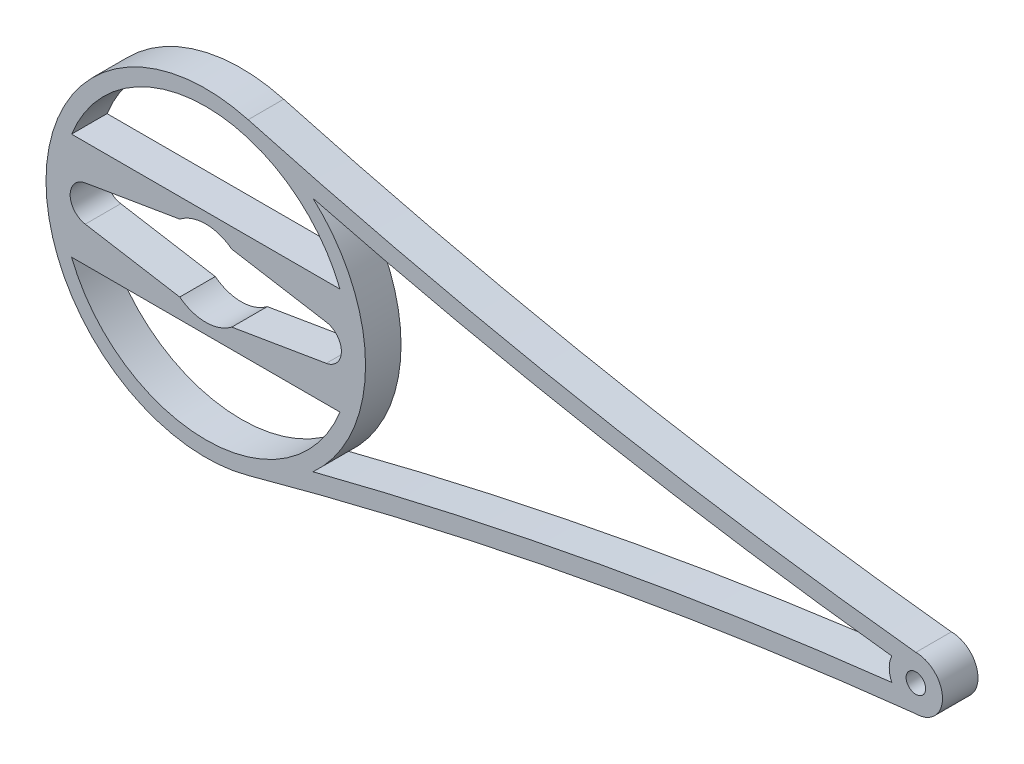
SolidWorks part; units mm, degrees
material "ABS"
ref_plane "Front Plane" through (0, 0, 0) normal (0, 0, 1) x (1, 0, 0)
ref_plane "Top Plane" through (0, 0, 0) normal (0, 1, 0) x (1, 0, 0)
ref_plane "Right Plane" through (0, 0, 0) normal (1, 0, 0) x (0, 0, -1)
sketch "Sketch3" plane through (0, 0, 0) normal (0, 0, 1) x (1, 0, 0)
  line L0 (0, 0) -> (100, 0) construction
  line L1 (18.9, 0) -> (18.9, 7.5) construction
  line L2 (-18.9, -7.5) -> (18.9, -7.5)
  line L3 (-18.9, -7.5) -> (-18.9, 7.5) construction
  line L4 (-18.9, 7.5) -> (18.9, 7.5)
  line L5 (18.9, -7.5) -> (18.9, 0) construction
  arc A0 (5.9672, 21.6943) -> (5.9672, -21.6943) centre (0, 0) ccw
  arc A1 (-18.9, -7.5) -> (18.9, -7.5) centre (0, 0) ccw
  arc A2 (100, -3.75) -> (100, 3.75) centre (100, 0) ccw
  arc A3 (5.9672, 21.6943) -> (100, 3.75) centre (165.0937, 600.2086) ccw
  arc A4 (15.1042, 16.6767) -> (96.6145, 1.6128) centre (165.0937, 600.2086) ccw
  arc A5 (5.3042, 19.2838) -> (99.7288, 1.2648) centre (165.0937, 600.2086) ccw construction
  arc A6 (15.1042, -16.6767) -> (96.6145, -1.6128) centre (165.0937, -600.2086) cw
  arc A7 (5.9672, -21.6943) -> (100, -3.75) centre (165.0937, -600.2086) cw
  arc A8 (96.6145, -1.6128) -> (100, -3.75) centre (100, 0) ccw construction
  arc A9 (100, 3.75) -> (96.6145, 1.6128) centre (100, 0) ccw construction
  arc A10 (96.6145, 1.6128) -> (96.6145, -1.6128) centre (100, 0) ccw
  arc A11 (15.1042, 16.6767) -> (5.9672, 21.6943) centre (0, 0) ccw construction
  arc A12 (5.9672, -21.6943) -> (15.1042, -16.6767) centre (0, 0) ccw construction
  arc A13 (15.1042, -16.6767) -> (15.1042, 16.6767) centre (0, 0) ccw
  arc A14 (-18.9, 7.5) -> (-18.9, -7.5) centre (0, 0) ccw construction
  arc A15 (20.3337, 0) -> (18.9, 7.5) centre (0, 0) ccw construction
  arc A16 (18.9, 7.5) -> (-18.9, 7.5) centre (0, 0) ccw
  arc A17 (18.9, -7.5) -> (20.3337, 0) centre (0, 0) ccw construction
  point P9 (-18.9, 0)
  point P19 (0, 7.5)
  dimension "D2" = 37.8
  dimension "D4" = 45
  dimension "D6" = 7.5
  dimension "D7" = 600
  dimension "D3" = 15
  dimension "D5" = 100
  dimension "D1" = 2.5
extrude "Boss-Extrude1" add sketch "Sketch3" along normal mid plane 5
sketch "Sketch4" plane through (0, 0, 2.5) normal (0, 0, 1) x (1, 0, 0)
  line L0 (16.55, 0) -> (-16.55, 0) construction
  line L1 (0, 0) -> (0, 6) construction
  line L2 (-16.9724, 2.5148) -> (-3.6657, 4.75)
  line L3 (-16.9724, -2.5148) -> (-3.6657, -4.75)
  line L4 (16.9724, -2.5148) -> (3.6657, -4.75)
  line L5 (16.9724, 2.5148) -> (3.6657, 4.75)
  line L6 (-16.55, 0) -> (-19.1, 0) construction
  arc A0 (-3.6657, -4.75) -> (3.6657, -4.75) centre (0, 0) ccw
  arc A1 (-16.9724, 2.5148) -> (-16.9724, -2.5148) centre (-16.55, 0) ccw
  arc A2 (-16.9724, -2.5148) -> (-14, 0) centre (-16.55, 0) ccw construction
  arc A3 (-14, 0) -> (-16.9724, 2.5148) centre (-16.55, 0) ccw construction
  arc A4 (-6, 0) -> (-3.6657, -4.75) centre (0, 0) ccw construction
  arc A5 (-3.6657, 4.75) -> (-6, 0) centre (0, 0) ccw construction
  arc A6 (14, 0) -> (16.9724, 2.5148) centre (16.55, 0) cw construction
  arc A7 (16.9724, -2.5148) -> (14, 0) centre (16.55, 0) cw construction
  arc A8 (16.9724, 2.5148) -> (16.9724, -2.5148) centre (16.55, 0) cw
  arc A9 (6, 0) -> (3.6657, 4.75) centre (0, 0) ccw construction
  arc A10 (3.6657, 4.75) -> (-3.6657, 4.75) centre (0, 0) ccw
  arc A11 (3.6657, -4.75) -> (6, 0) centre (0, 0) ccw construction
  dimension "D1" = 12
  dimension "D2" = 5.1
  dimension "D3" = 19.1
  dimension "D4" = 9.5
extrude "Cut-Extrude1" cut sketch "Sketch4" against normal through all
sketch "Sketch6" plane through (0, 0, 0) normal (0, 0, 1) x (1, 0, 0)
  circle A0 centre (100, 0) radius 1.375
  dimension "D1" = 2.75
extrude "Cut-Extrude2" cut sketch "Sketch6" against normal through all both and the other way through all
